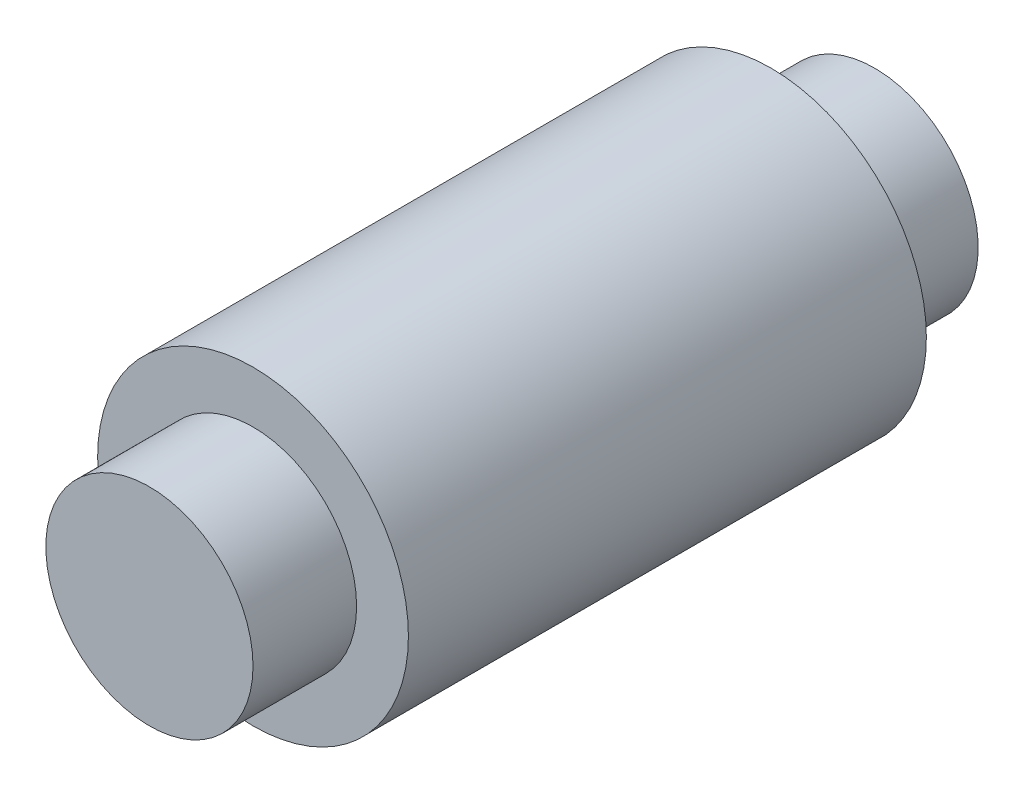
SolidWorks part; units mm, degrees
ref_plane "Front Plane" through (0, 0, 0) normal (0, 0, 1) x (1, 0, 0)
ref_plane "Top Plane" through (0, 0, 0) normal (0, 1, 0) x (1, 0, 0)
ref_plane "Right Plane" through (0, 0, 0) normal (1, 0, 0) x (0, 0, -1)
sketch "Sketch1" plane through (0, 0, 0) normal (0, 0, 1) x (1, 0, 0)
  circle A0 centre (0, 0) radius 150
  dimension "D1" = 300
extrude "Boss-Extrude1" add sketch "Sketch1" along normal blind 500
sketch "Sketch2" plane through (0, 0, 500) normal (0, 0, 1) x (1, 0, 0)
  circle A0 centre (0, 0) radius 100
  dimension "D1" = 200
extrude "Boss-Extrude2" add sketch "Sketch2" along normal blind 100
sketch "Sketch3" plane through (0, 0, 0) normal (0, 0, -1) x (-1, 0, 0)
  circle A0 centre (0, 0) radius 100
  dimension "D1" = 200
extrude "Boss-Extrude3" add sketch "Sketch3" along normal blind 100
